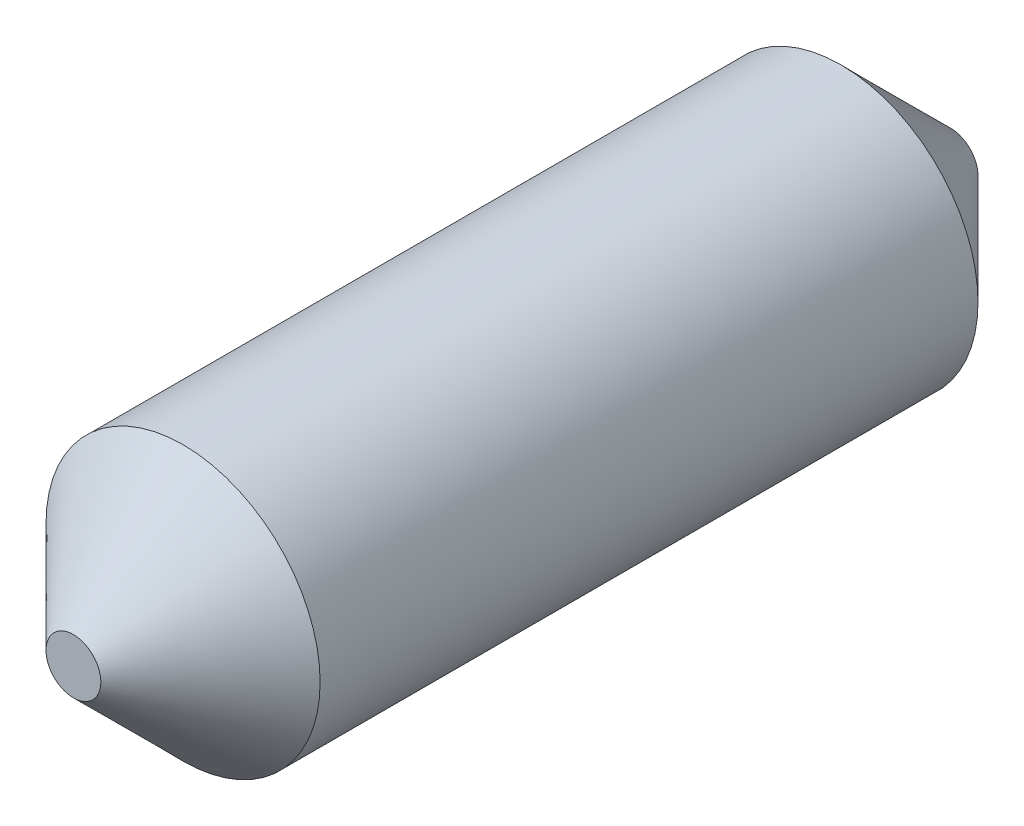
SolidWorks part; units mm, degrees
ref_plane "Front Plane" through (0, 0, 0) normal (0, 0, 1) x (1, 0, 0)
ref_plane "Top Plane" through (0, 0, 0) normal (0, 1, 0) x (1, 0, 0)
ref_plane "Right Plane" through (0, 0, 0) normal (1, 0, 0) x (0, 0, -1)
sketch "Sketch1" plane through (0, 0, 0) normal (0, 0, 1) x (1, 0, 0)
  circle A0 centre (0, 0) radius 1.25
  dimension "D1" = 2.5
extrude "Boss-Extrude1" add sketch "Sketch1" along normal blind 8
chamfer "Chamfer1" distance 1 angle 45 2 edges at (1.25, 0, 8) (1.25, 0, 0)
